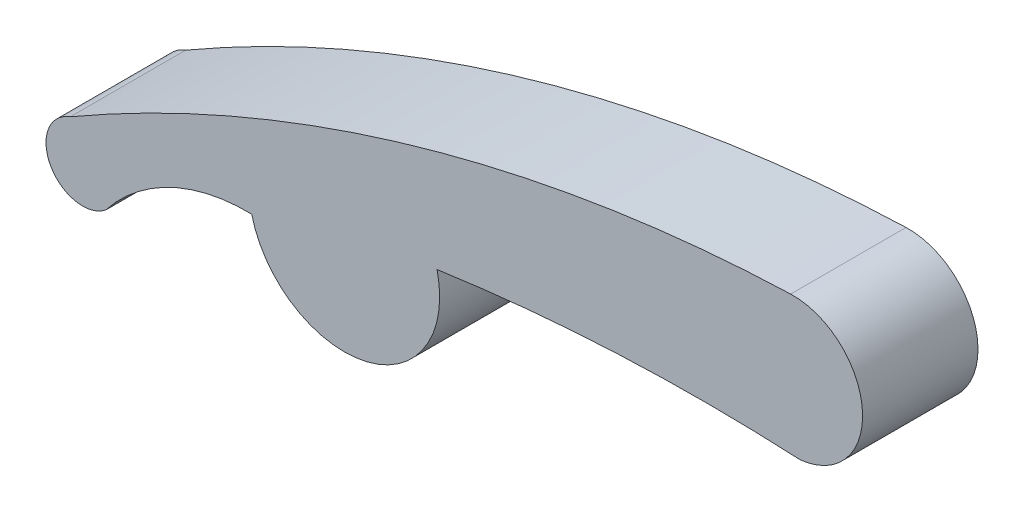
SolidWorks part; units mm, degrees
ref_plane "前视基准面" through (0, 0, 0) normal (0, 0, 1) x (1, 0, 0)
ref_plane "上视基准面" through (0, 0, 0) normal (0, 1, 0) x (1, 0, 0)
ref_plane "右视基准面" through (0, 0, 0) normal (1, 0, 0) x (0, 0, -1)
other "Configuration Table"
sketch "草图2" plane through (0, 0, 0) normal (0, 0, 1) x (1, 0, 0)
  arc A0 (-61.9925, -23.8028) -> (-24.0879, -5.8145) centre (-25.1623, -52.4806) cw
  arc A1 (-24.0879, -5.8145) -> (24.0868, 5.819) centre (0, 0) ccw
  arc A2 (24.0868, 5.819) -> (118.483, 10.1801) centre (93.5548, -474.0352) cw
  arc A3 (116.0305, 46.2617) -> (118.483, 10.1801) centre (116.6445, 28.1793) cw
  arc A4 (-71.2994, -7.4803) -> (116.0305, 46.2617) centre (129.6397, -354.5371) cw
  arc A5 (-71.2994, -7.4803) -> (-61.9925, -23.8028) centre (-68.0426, -16.4379) ccw
  dimension "D1" = 120
  dimension "D2" = 70
extrude "凸台-拉伸1" add sketch "草图2" along normal blind 30
